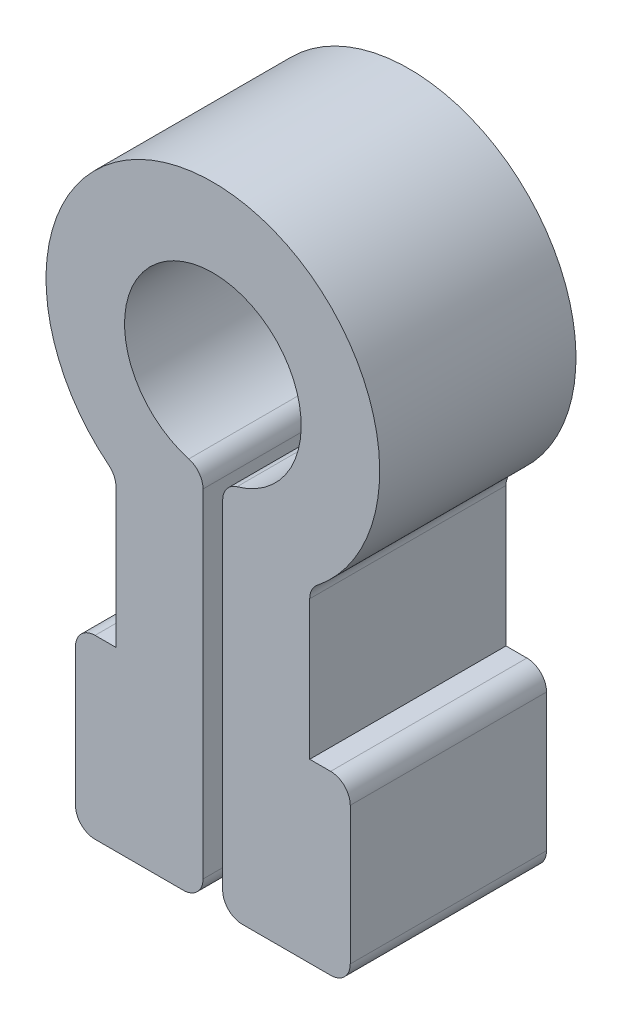
SolidWorks part; units mm, degrees
ref_plane "Alzado" through (0, 0, 0) normal (0, 0, 1) x (1, 0, 0)
ref_plane "Planta" through (0, 0, 0) normal (0, 1, 0) x (1, 0, 0)
ref_plane "Vista lateral" through (0, 0, 0) normal (1, 0, 0) x (0, 0, -1)
sketch "Croquis1" plane through (0, 0, 0) normal (0, 0, 1) x (1, 0, 0)
  line L0 (1.5, -23.5) -> (6, -23.5)
  line L1 (-0.5, -5.2915) -> (-0.5, -22.5)
  line L2 (0.5, -5.2915) -> (0.5, -22.5)
  line L3 (-7, -22.5) -> (-7, -15.5)
  line L4 (-6, -14.5) -> (-4.9346, -14.5)
  line L5 (7, -22.5) -> (7, -15.5)
  line L6 (6, -14.5) -> (4.9346, -14.5)
  line L7 (-4.9346, -14.5) -> (-4.9346, -7.4183)
  line L8 (4.9346, -14.5) -> (4.9346, -7.4183)
  line L9 (-6, -23.5) -> (-1.5, -23.5)
  arc A0 (1.2273, -4.3294) -> (-1.2273, -4.3294) centre (0, 0) ccw
  arc A1 (5.3099, -6.6374) -> (-5.3099, -6.6374) centre (0, 0) ccw
  circle A6 centre (0, 0) radius 4.5 construction
  circle A8 centre (0, 0) radius 8.5 construction
  arc A9 (-0.5, -5.2915) -> (-1.2273, -4.3294) centre (-1.5, -5.2915) ccw
  arc A10 (6, -23.5) -> (7, -22.5) centre (6, -22.5) ccw
  arc A11 (1.5, -23.5) -> (0.5, -22.5) centre (1.5, -22.5) cw
  arc A12 (-1.5, -23.5) -> (-0.5, -22.5) centre (-1.5, -22.5) ccw
  arc A13 (-6, -23.5) -> (-7, -22.5) centre (-6, -22.5) cw
  arc A14 (-7, -15.5) -> (-6, -14.5) centre (-6, -15.5) cw
  arc A15 (7, -15.5) -> (6, -14.5) centre (6, -15.5) ccw
  arc A16 (4.9346, -7.4183) -> (5.3099, -6.6374) centre (5.9346, -7.4183) cw
  arc A17 (-4.9346, -7.4183) -> (-5.3099, -6.6374) centre (-5.9346, -7.4183) ccw
  arc A18 (0.5, -5.2915) -> (1.2273, -4.3294) centre (1.5, -5.2915) cw
  point P4 (0, 0)
  point P9 (0, 0)
  point P29 (0.5, -23.5)
  point P34 (-7, -23.5)
  point P37 (-7, -14.5)
  point P47 (0, 8.5)
  point P48 (-3.75, -23.5)
  dimension "D1" = 9
  dimension "D3" = 4.5
  dimension "D4" = 1
  dimension "D5" = 1
  dimension "D2" = 14
  dimension "D6" = 32
extrude "Saliente-Extruir1" add sketch "Croquis1" along normal blind 10 contours A0 A9 L1 A12 L9 A13 L3 A14 L4 L7 A17 A1 A16 L8 L6 A15 L5 A10 L0 A11 L2 A18
